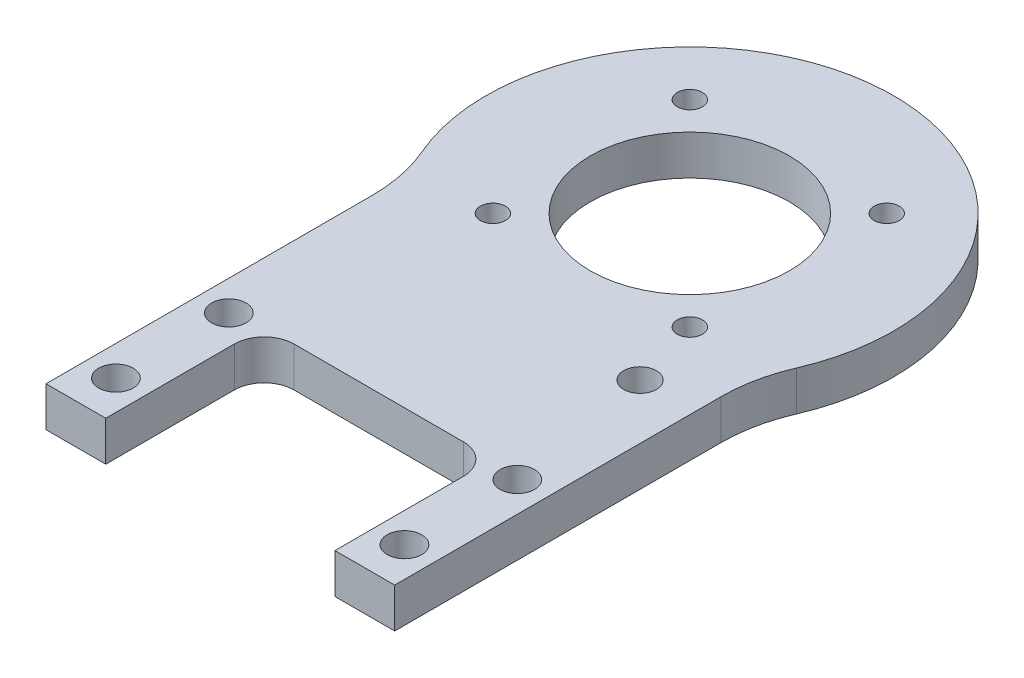
SolidWorks part; units mm, degrees
ref_plane "Front Plane" through (0, 0, 0) normal (0, 0, 1) x (1, 0, 0)
ref_plane "Top Plane" through (0, 0, 0) normal (0, 1, 0) x (1, 0, 0)
ref_plane "Right Plane" through (0, 0, 0) normal (1, 0, 0) x (0, 0, -1)
sketch "Sketch1" plane through (0, 594.769, 0) normal (0, 1, 0) x (1, 0, 0)
  line L0 (17, -50.5515) -> (17, -80.0303) construction
  line L1 (-14.7394, -48.2909) -> (14.7394, -48.2909) construction
  line L2 (-17, -80.0303) -> (-17, -50.5515) construction
  line L3 (17, -50.5515) -> (17, -80.0303) construction
  line L4 (-14.7394, -48.2909) -> (14.7394, -48.2909) construction
  line L5 (-17, -80.0303) -> (-17, -50.5515) construction
  line L6 (18.27, -51.1484) -> (18.27, -71.6409)
  line L7 (18.27, -71.6409) -> (27.795, -71.6409)
  line L8 (27.795, -71.6409) -> (27.795, -19.6561)
  line L9 (0, -46.3859) -> (13.5075, -46.3859)
  line L10 (18.27, -50.5515) -> (18.27, -80.0303) construction
  line L11 (-14.7394, -46.3859) -> (14.7394, -46.3859) construction
  line L12 (0, -48.2909) -> (0, -46.3859) construction
  line L13 (-27.795, -71.6409) -> (-27.795, -19.6561)
  line L14 (-18.27, -71.6409) -> (-27.795, -71.6409)
  line L15 (-18.27, -51.1484) -> (-18.27, -71.6409)
  line L16 (0, -46.3859) -> (-13.5075, -46.3859)
  line L17 (-17, -65.2909) -> (17, -65.2909) construction
  line L18 (0, -65.2909) -> (0, 3.2066) construction
  line L19 (0, 3.2066) -> (-15.6978, -12.4912) construction
  line L20 (-33.3375, -30.1309) -> (-33.3375, 36.5441)
  line L21 (-33.3375, -30.1309) -> (-33.3375, 36.5441) construction
  line L22 (-33.3375, 36.5441) -> (33.3375, 36.5441)
  line L23 (-33.3375, 36.5441) -> (33.3375, 36.5441) construction
  line L24 (33.3375, 36.5441) -> (33.3375, -30.1309)
  line L25 (33.3375, 36.5441) -> (33.3375, -30.1309) construction
  line L26 (-33.3375, 36.5441) -> (33.3375, -30.1309) construction
  circle A0 centre (-23, -65.2909) radius 2.75 construction
  circle A1 centre (-23, -47.2909) radius 2.75 construction
  circle A2 centre (23, -47.2909) radius 2.75 construction
  circle A3 centre (23, -65.2909) radius 2.75 construction
  circle A4 centre (-23, -65.2909) radius 2.75
  circle A5 centre (-23, -47.2909) radius 2.75
  circle A6 centre (23, -47.2909) radius 2.75
  circle A7 centre (23, -65.2909) radius 2.75
  arc A8 (18.27, -51.1484) -> (13.5075, -46.3859) centre (13.5075, -51.1484) ccw
  arc A9 (-18.27, -51.1484) -> (-13.5075, -46.3859) centre (-13.5075, -51.1484) cw
  circle A10 centre (0, 3.2066) radius 15.875
  circle A11 centre (-15.6978, -12.4912) radius 2
  circle A12 centre (-15.6978, 18.9043) radius 2
  circle A13 centre (15.6978, 18.9043) radius 2
  circle A14 centre (15.6978, -12.4912) radius 2
  arc A15 (-29.859, -9.6265) -> (29.859, -9.6265) centre (0, 3.2066) cw
  arc A16 (29.859, -9.6265) -> (27.795, -19.6561) centre (53.195, -19.6561) ccw
  arc A17 (-29.859, -9.6265) -> (-27.795, -19.6561) centre (-53.195, -19.6561) cw
  point P29 (-33.3375, 32.5)
  point P44 (33.3375, 32.5)
  point P53 (0, 3.2066)
  point P56 (27.795, -13.6365)
  point P59 (-27.795, -13.6365)
  point P77 (27.7375, 27.7375)
  point P78 (27.7375, -5.95)
  point P83 (-27.7375, 27.7375)
  point P84 (-27.7375, -5.95)
  dimension "D5" = 4.7625
  dimension "D7" = 31.75
  dimension "D10" = 4
  dimension "D12" = 32.5
  dimension "D13" = 25.4
  dimension "D2" = 9.525
  dimension "D3" = 6.35
  dimension "D8" = 45
  dimension "D9" = 22.2
  dimension "D1" = 1.27
  dimension "D4" = 1.905
  dimension "D11" = 4
extrude "Boss-Extrude1" add sketch "Sketch1" along normal blind 6.35
sketch "Sketch2" plane through (0, 601.119, 0) normal (0, 1, 0) x (1, 0, 0)
  line L0 (-24.3646, -60.9791) -> (-12.6107, 5.4383) construction
  line L1 (8.1482, -21.6273) -> (12.5638, 0.7246) construction
  line L2 (9.1553, -28.8388) -> (22.0317, -54.029) construction
  line L7 (-27.795, -19.6561) -> (-27.795, -71.6409)
  line L8 (-27.795, -71.6409) -> (-18.27, -71.6409)
  line L9 (-18.27, -71.6409) -> (-18.27, -51.1484)
  line L10 (-13.5075, -46.3859) -> (13.5075, -46.3859)
  line L11 (18.27, -51.1484) -> (18.27, -71.6409)
  line L12 (18.27, -71.6409) -> (27.795, -71.6409)
  line L13 (27.795, -71.6409) -> (27.795, -19.6561)
  line L14 (-27.795, -19.6561) -> (-27.795, -71.6409) construction
  line L15 (-27.795, -71.6409) -> (-18.27, -71.6409) construction
  line L16 (-18.27, -71.6409) -> (-18.27, -51.1484) construction
  line L17 (-13.5075, -46.3859) -> (13.5075, -46.3859) construction
  line L18 (18.27, -51.1484) -> (18.27, -71.6409) construction
  line L19 (18.27, -71.6409) -> (27.795, -71.6409) construction
  line L20 (27.795, -71.6409) -> (27.795, -19.6561) construction
  circle A0 centre (0, 3.2066) radius 12.8066 construction
  arc A1 (12.5638, 0.7246) -> (-12.6107, 5.4383) centre (0, 3.2066) ccw construction
  circle A2 centre (0, -65.2909) radius 24.7432 construction
  arc A3 (-24.3646, -60.9791) -> (22.0317, -54.029) centre (0, -65.2909) ccw construction
  circle A4 centre (19.05, -23.7809) radius 2.6035
  arc A5 (29.859, -9.6265) -> (-29.859, -9.6265) centre (0, 3.2066) ccw
  arc A6 (-27.795, -19.6561) -> (-29.859, -9.6265) centre (-53.195, -19.6561) ccw
  arc A7 (-13.5075, -46.3859) -> (-18.27, -51.1484) centre (-13.5075, -51.1484) ccw
  arc A8 (18.27, -51.1484) -> (13.5075, -46.3859) centre (13.5075, -51.1484) ccw
  arc A9 (29.859, -9.6265) -> (27.795, -19.6561) centre (53.195, -19.6561) ccw
  arc A10 (29.859, -9.6265) -> (-29.859, -9.6265) centre (0, 3.2066) ccw construction
  arc A11 (-27.795, -19.6561) -> (-29.859, -9.6265) centre (-53.195, -19.6561) ccw construction
  arc A12 (-13.5075, -46.3859) -> (-18.27, -51.1484) centre (-13.5075, -51.1484) ccw construction
  arc A13 (18.27, -51.1484) -> (13.5075, -46.3859) centre (13.5075, -51.1484) ccw construction
  arc A14 (29.859, -9.6265) -> (27.795, -19.6561) centre (53.195, -19.6561) ccw construction
  arc A15 (9.1553, -28.8388) -> (8.1482, -21.6273) centre (19.05, -23.7809) cw construction
  circle A16 centre (19.05, -23.7809) radius 11.1125 construction
  circle A17 centre (19.05, -23.7809) radius 11.1125 construction
  dimension "D2" = 5.207
  dimension "D3" = 26.9875
  dimension "D4" = 19.05
  dimension "D1" = 0
extrude "Cut-Extrude1" cut sketch "Sketch2" against normal up to surface (6.35 mm away) up to face at (0, 594.769, 12.6684)
